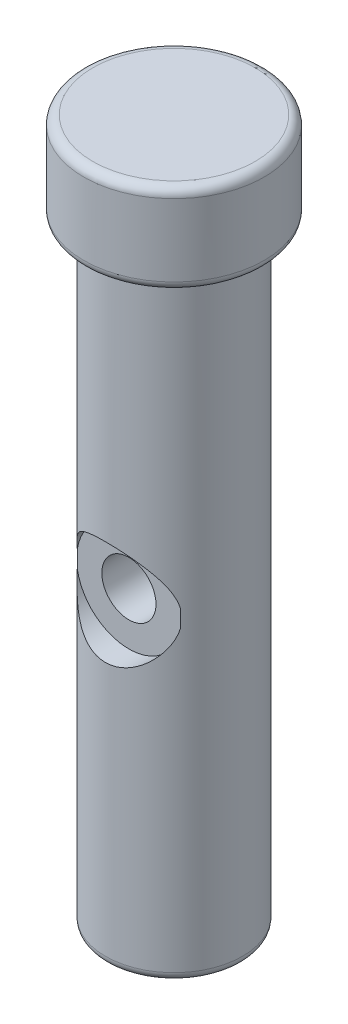
SolidWorks part; units mm, degrees
ref_plane "Ebene vorne" through (0, 0, 0) normal (0, 0, 1) x (1, 0, 0)
ref_plane "Ebene oben" through (0, 0, 0) normal (0, 1, 0) x (1, 0, 0)
ref_plane "Ebene rechts" through (0, 0, 0) normal (1, 0, 0) x (0, 0, -1)
sketch "Skizze1" plane through (0, 0, 0) normal (0, 0, 1) x (1, 0, 0)
  line L0 (0, 0) -> (0, -38)
  line L1 (0, -38) -> (-1.8, -38)
  line L2 (-1.8, -38) -> (-1.8, -39)
  line L3 (-1.8, -39) -> (-3.8, -39)
  line L4 (-3.8, -39) -> (-3.8, -5)
  line L5 (-3.8, -5) -> (-5, -5)
  line L6 (-5, -5) -> (-5, 0)
  line L7 (-5, 0) -> (0, 0)
  dimension "D1" = 5
  dimension "D2" = 3.8
  dimension "D3" = 5
  dimension "D4" = 38
  dimension "D5" = 1
  dimension "D6" = 1.8
revolve "Rotation1" add sketch "Skizze1" angle 360 about L0
fillet "Verrundung1" radius 0.5 4 edges at (-1.8, -39, 0) (-3.8, -39, 0) (-5, 0, 0) (-5, -5, 0)
sketch "Skizze2" plane through (0, 0, 0) normal (0, 0, 1) x (1, 0, 0)
  line L0 (4.5, 0) -> (-4.5, 0) construction
  line L1 (0, 47.2841) -> (0, -783.6342) construction
  circle A0 centre (0, -21.5) radius 1.5
  point P4 (0, 0)
  dimension "D1" = 3
  dimension "D2" = 21.5
extrude "Schnitt-Linear austragen1" cut sketch "Skizze2" against normal through all and the other way through all
ref_plane "Ebene1" through (0, 0, 2.5) normal (0, 0, 1) x (1, 0, 0)
sketch "Skizze3" plane through (0, 0, 2.5) normal (0, 0, 1) x (1, 0, 0)
  circle A0 centre (0, -21.5) radius 2.9
  circle A1 centre (0, -21.5) radius 1.5 construction
  dimension "D1" = 5.8
extrude "Schnitt-Linear austragen10" cut sketch "Skizze3" along normal through all
